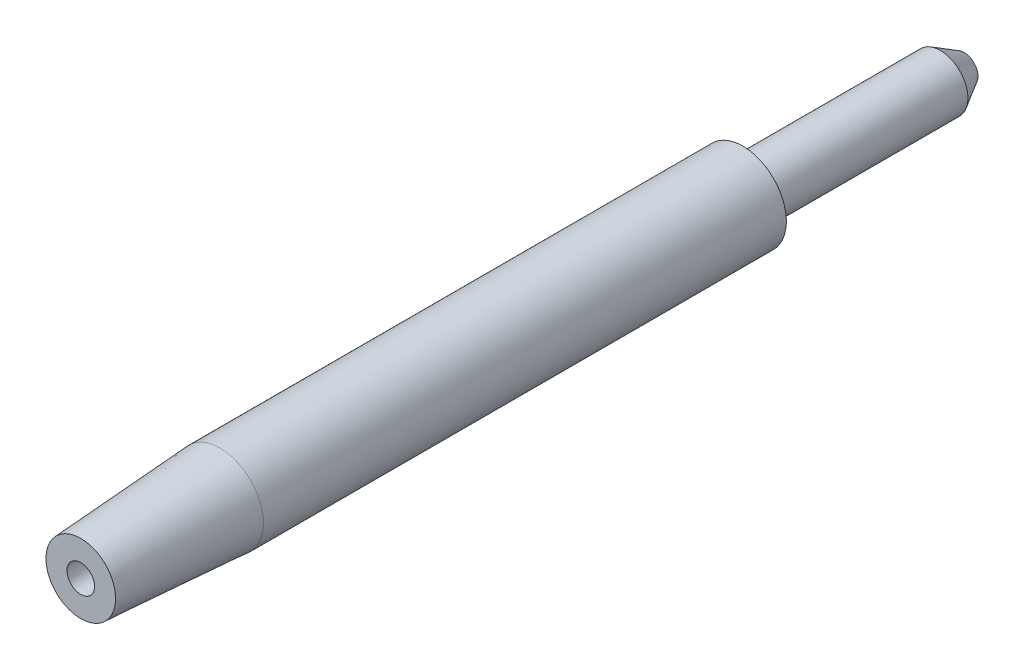
SolidWorks part; units mm, degrees
ref_plane "Front Plane" through (0, 0, 0) normal (0, 0, 1) x (1, 0, 0)
ref_plane "Top Plane" through (0, 0, 0) normal (0, 1, 0) x (1, 0, 0)
ref_plane "Right Plane" through (0, 0, 0) normal (1, 0, 0) x (0, 0, -1)
sketch "Sketch1" plane through (0, 0, 0) normal (0, 1, 0) x (1, 0, 0)
  line L0 (-5.4766, 0.0271) -> (-5.4766, -50.7667)
  line L1 (-6.2704, -1.3477) -> (-5.4766, 0.0271)
  line L2 (-4.6829, 12.7333) -> (-4.6829, -50.7667) construction
  line L3 (-5.4766, -42.7667) -> (-7.9766, -42.7667) construction
  line L4 (-7.1829, -42.7667) -> (-6.6829, -50.7667)
  line L5 (-6.2704, -50.7667) -> (-6.2704, 0) construction
  line L6 (-7.1829, -42.7667) -> (-7.1829, -12.7)
  line L7 (-6.2704, -12.7) -> (-6.2704, -1.3477)
  line L8 (-6.2704, -12.7) -> (-7.1829, -12.7)
  line L11 (-6.6829, -50.7667) -> (-5.4766, -50.7667)
  circle A0 centre (-4.6829, -50.7667) radius 0.7937 construction
  circle A1 centre (-4.6829, -50.7667) radius 1.5875 construction
  circle A2 centre (-4.6829, -42.7667) radius 2.5 construction
  circle A3 centre (-4.6829, -50.7667) radius 2 construction
  dimension "D2" = 8
  dimension "D5" = 1.5875
  dimension "D6" = 3.175
  dimension "D7" = 4
  dimension "D4" = 5
revolve "Revolve1" add sketch "Sketch1" angle 360 about L2
